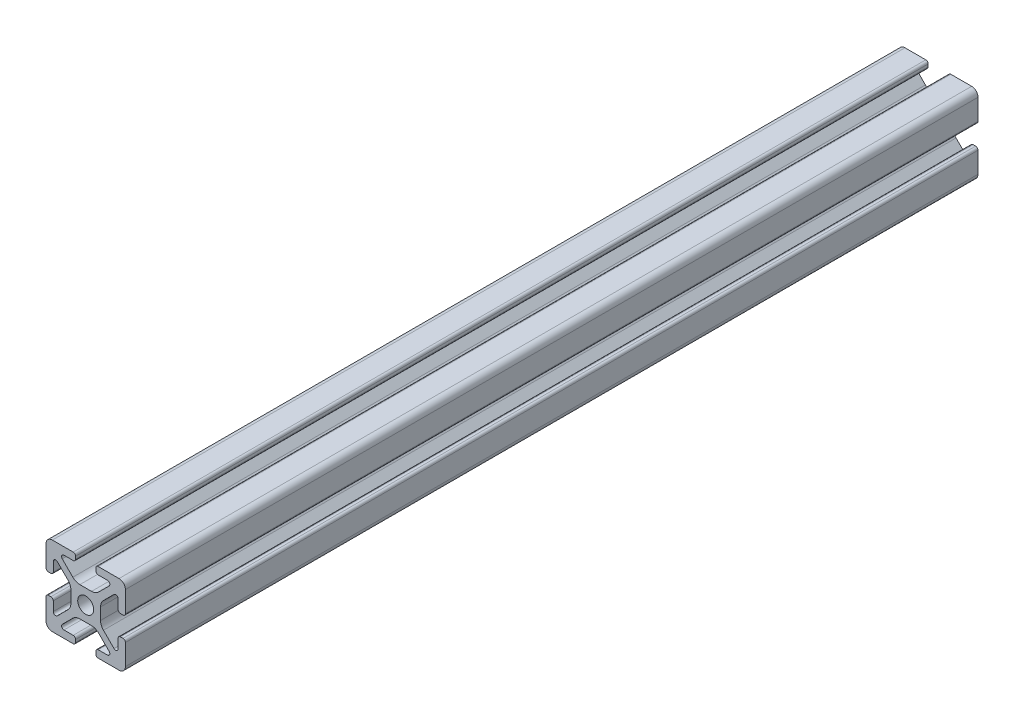
SolidWorks part; units mm, degrees
material "6063-T6"
ref_plane "Front" through (0, 0, 0) normal (0, 0, 1) x (1, 0, 0)
ref_plane "Top" through (0, 0, 0) normal (0, 1, 0) x (1, 0, 0)
ref_plane "Right" through (0, 0, 0) normal (1, 0, 0) x (0, 0, -1)
sketch "Sketch1" plane through (0, 0, 0) normal (0, 0, 1) x (1, 0, 0)
  line L0 (0, 0) -> (-63.6357, 63.6357) construction
  line L1 (0, 0) -> (53.0782, 0) construction
  line L2 (69.577, 69.577) -> (0, 0) construction
  line L3 (-7.4998, 9.0624) -> (-4.1172, 5.6797)
  line L4 (-12.7, 12.7) -> (6.1576, 12.7) construction
  line L5 (-1.8721, 4.7498) -> (1.8721, 4.7498)
  line L6 (4.1172, 5.6797) -> (7.4998, 9.0624)
  line L7 (-3.2385, 11.938) -> (-3.2385, 11.1252)
  line L8 (-11.938, -3.2385) -> (-11.1252, -3.2385)
  line L9 (-10.668, 12.7) -> (-4.0005, 12.7)
  line L10 (10.668, 12.7) -> (4.0005, 12.7)
  line L11 (-6.961, 10.3632) -> (-4.0005, 10.3632)
  line L12 (6.961, 10.3632) -> (4.0005, 10.3632)
  line L13 (3.2385, 11.938) -> (3.2385, 11.1252)
  line L14 (-10.3632, -6.961) -> (-10.3632, -4.0005)
  line L15 (-10.3632, 6.961) -> (-10.3632, 4.0005)
  line L16 (-12.7, -10.668) -> (-12.7, -4.0005)
  line L17 (-12.7, 10.668) -> (-12.7, 4.0005)
  line L18 (-11.938, 3.2385) -> (-11.1252, 3.2385)
  line L19 (-5.6797, -4.1172) -> (-9.0624, -7.4998)
  line L20 (-4.7498, 1.8721) -> (-4.7498, -1.8721)
  line L21 (-9.0624, 7.4998) -> (-5.6797, 4.1172)
  line L22 (7.4998, -9.0624) -> (4.1172, -5.6797)
  line L23 (1.8721, -4.7498) -> (-1.8721, -4.7498)
  line L24 (-4.1172, -5.6797) -> (-7.4998, -9.0624)
  line L25 (3.2385, -11.938) -> (3.2385, -11.1252)
  line L26 (10.668, -12.7) -> (4.0005, -12.7)
  line L27 (-10.668, -12.7) -> (-4.0005, -12.7)
  line L28 (6.961, -10.3632) -> (4.0005, -10.3632)
  line L29 (-6.961, -10.3632) -> (-4.0005, -10.3632)
  line L30 (11.938, 3.2385) -> (11.1252, 3.2385)
  line L31 (10.3632, 6.961) -> (10.3632, 4.0005)
  line L32 (10.3632, -6.961) -> (10.3632, -4.0005)
  line L33 (12.7, 10.668) -> (12.7, 4.0005)
  line L34 (12.7, -10.668) -> (12.7, -4.0005)
  line L35 (-3.2385, -11.938) -> (-3.2385, -11.1252)
  line L36 (11.938, -3.2385) -> (11.1252, -3.2385)
  line L37 (5.6797, 4.1172) -> (9.0624, 7.4998)
  line L38 (4.7498, -1.8721) -> (4.7498, 1.8721)
  line L39 (9.0624, -7.4998) -> (5.6797, -4.1172)
  line L40 (-12.7, 12.7) -> (-12.7, 2.6899) construction
  circle A0 centre (0, 0) radius 2.5527
  arc A1 (-10.668, 12.7) -> (-12.7, 10.668) centre (-10.668, 10.668) ccw
  arc A2 (12.7, 10.668) -> (10.668, 12.7) centre (10.668, 10.668) ccw
  arc A3 (7.4998, 9.0624) -> (6.961, 10.3632) centre (6.961, 9.6012) ccw
  arc A4 (3.2385, 11.1252) -> (4.0005, 10.3632) centre (4.0005, 11.1252) ccw
  arc A5 (3.2385, 11.938) -> (4.0005, 12.7) centre (4.0005, 11.938) cw
  arc A6 (-3.2385, 11.938) -> (-4.0005, 12.7) centre (-4.0005, 11.938) ccw
  arc A7 (-4.0005, 10.3632) -> (-3.2385, 11.1252) centre (-4.0005, 11.1252) ccw
  arc A8 (-7.4998, 9.0624) -> (-6.961, 10.3632) centre (-6.961, 9.6012) cw
  arc A9 (1.8721, 4.7498) -> (4.1172, 5.6797) centre (1.8721, 7.9248) ccw
  arc A10 (-4.1172, 5.6797) -> (-1.8721, 4.7498) centre (-1.8721, 7.9248) ccw
  arc A11 (-5.6797, 4.1172) -> (-4.7498, 1.8721) centre (-7.9248, 1.8721) cw
  arc A12 (-4.7498, -1.8721) -> (-5.6797, -4.1172) centre (-7.9248, -1.8721) cw
  arc A13 (-9.0624, 7.4998) -> (-10.3632, 6.961) centre (-9.6012, 6.961) ccw
  arc A14 (-10.3632, 4.0005) -> (-11.1252, 3.2385) centre (-11.1252, 4.0005) cw
  arc A15 (-11.938, 3.2385) -> (-12.7, 4.0005) centre (-11.938, 4.0005) cw
  arc A16 (-11.938, -3.2385) -> (-12.7, -4.0005) centre (-11.938, -4.0005) ccw
  arc A17 (-11.1252, -3.2385) -> (-10.3632, -4.0005) centre (-11.1252, -4.0005) cw
  arc A18 (-9.0624, -7.4998) -> (-10.3632, -6.961) centre (-9.6012, -6.961) cw
  arc A19 (-10.668, -12.7) -> (-12.7, -10.668) centre (-10.668, -10.668) cw
  arc A20 (-7.4998, -9.0624) -> (-6.961, -10.3632) centre (-6.961, -9.6012) ccw
  arc A21 (-3.2385, -11.1252) -> (-4.0005, -10.3632) centre (-4.0005, -11.1252) ccw
  arc A22 (-3.2385, -11.938) -> (-4.0005, -12.7) centre (-4.0005, -11.938) cw
  arc A23 (3.2385, -11.938) -> (4.0005, -12.7) centre (4.0005, -11.938) ccw
  arc A24 (4.0005, -10.3632) -> (3.2385, -11.1252) centre (4.0005, -11.1252) ccw
  arc A25 (7.4998, -9.0624) -> (6.961, -10.3632) centre (6.961, -9.6012) cw
  arc A26 (-1.8721, -4.7498) -> (-4.1172, -5.6797) centre (-1.8721, -7.9248) ccw
  arc A27 (4.1172, -5.6797) -> (1.8721, -4.7498) centre (1.8721, -7.9248) ccw
  arc A28 (5.6797, -4.1172) -> (4.7498, -1.8721) centre (7.9248, -1.8721) cw
  arc A29 (4.7498, 1.8721) -> (5.6797, 4.1172) centre (7.9248, 1.8721) cw
  arc A30 (9.0624, -7.4998) -> (10.3632, -6.961) centre (9.6012, -6.961) ccw
  arc A31 (10.3632, -4.0005) -> (11.1252, -3.2385) centre (11.1252, -4.0005) cw
  arc A32 (11.938, -3.2385) -> (12.7, -4.0005) centre (11.938, -4.0005) cw
  arc A33 (11.938, 3.2385) -> (12.7, 4.0005) centre (11.938, 4.0005) ccw
  arc A34 (11.1252, 3.2385) -> (10.3632, 4.0005) centre (11.1252, 4.0005) cw
  arc A35 (9.0624, 7.4998) -> (10.3632, 6.961) centre (9.6012, 6.961) cw
  arc A36 (12.7, -10.668) -> (10.668, -12.7) centre (10.668, -10.668) cw
  point P21 (-12.7266, 12.7266)
  point P22 (12.7, 12.7)
  dimension "D3" = 5.1054
  dimension "D5" = 2.032
  dimension "D13" = 0.762
  dimension "D15" = 3.175
  dimension "D14" = 5.6134
  dimension "D1" = 45
  dimension "D2" = 90
  dimension "D4" = 12.7
  dimension "D6" = 2.2098
  dimension "D7" = 2.2098
  dimension "D8" = 6.477
  dimension "D9" = 9.4615
  dimension "D10" = 0
  dimension "D11" = 7.9502
  dimension "D12" = 7.9502
  dimension "D16" = 9.4615
  dimension "D17" = 0
extrude "Boss-Extrude1" add sketch "Sketch1" along normal blind 272.796
sketch "Sketch2" plane through (0, 0, 0) normal (0, 0, 1) x (1, 0, 0)
  line L0 (-7.3202, 8.8828) -> (-7.3202, 8.5236)
  line L1 (-7.3202, 8.5236) -> (-6.961, 8.5236)
  line L2 (-6.961, 8.5236) -> (-7.3202, 8.8828)
  line L3 (-4.1172, 5.6797) -> (-7.4998, 9.0624) construction
  dimension "D1" = 0.254
  dimension "D2" = 0.254
extrude "Cut-Extrude2" [suppressed] cut sketch "Sketch2" along normal through all
